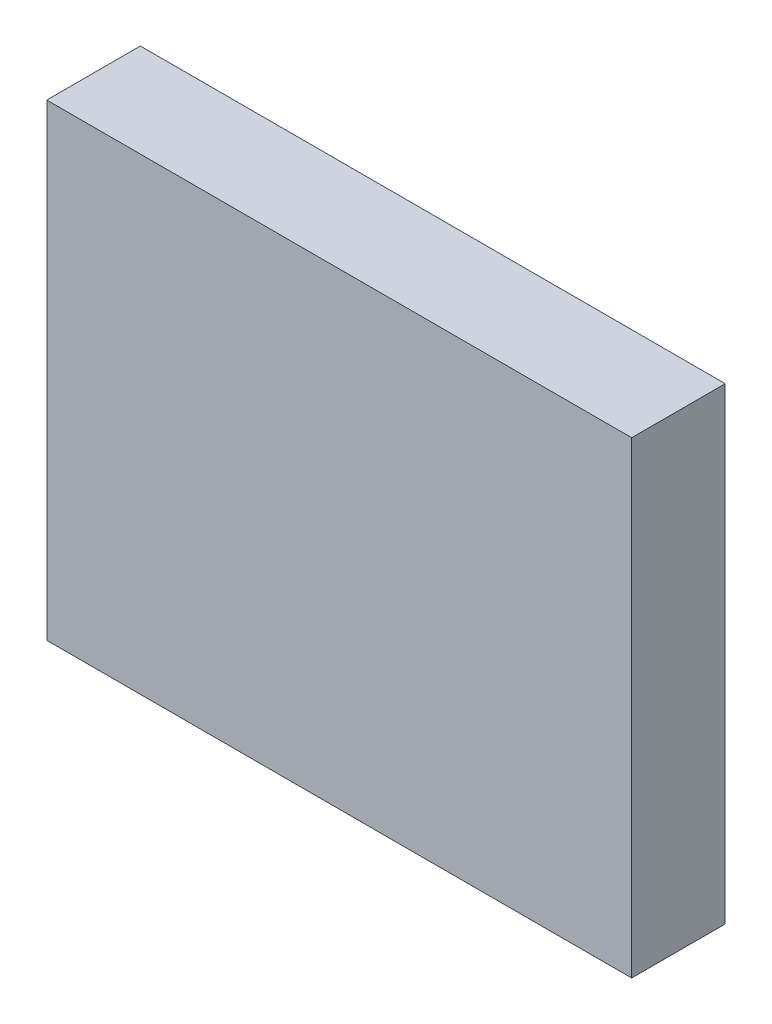
SolidWorks part; units mm, degrees
ref_plane "Front Plane" through (0, 0, 0) normal (0, 0, 1) x (1, 0, 0)
ref_plane "Top Plane" through (0, 0, 0) normal (0, 1, 0) x (1, 0, 0)
ref_plane "Right Plane" through (0, 0, 0) normal (1, 0, 0) x (0, 0, -1)
sketch "Sketch1" plane through (0, 0, 0) normal (0, 0, 1) x (1, 0, 0)
  line L1 (-25, 20) -> (25, 20)
  line L2 (-25, 20) -> (-25, -20)
  line L3 (-25, -20) -> (25, -20)
  line L4 (25, 20) -> (25, -20)
  line L5 (-25, 20) -> (25, -20) construction
  line L6 (-25, -20) -> (25, 20) construction
  point P0 (0, 0)
  dimension "D1" = 50
  dimension "D2" = 40
extrude "Boss-Extrude1" add sketch "Sketch1" along normal blind 8
